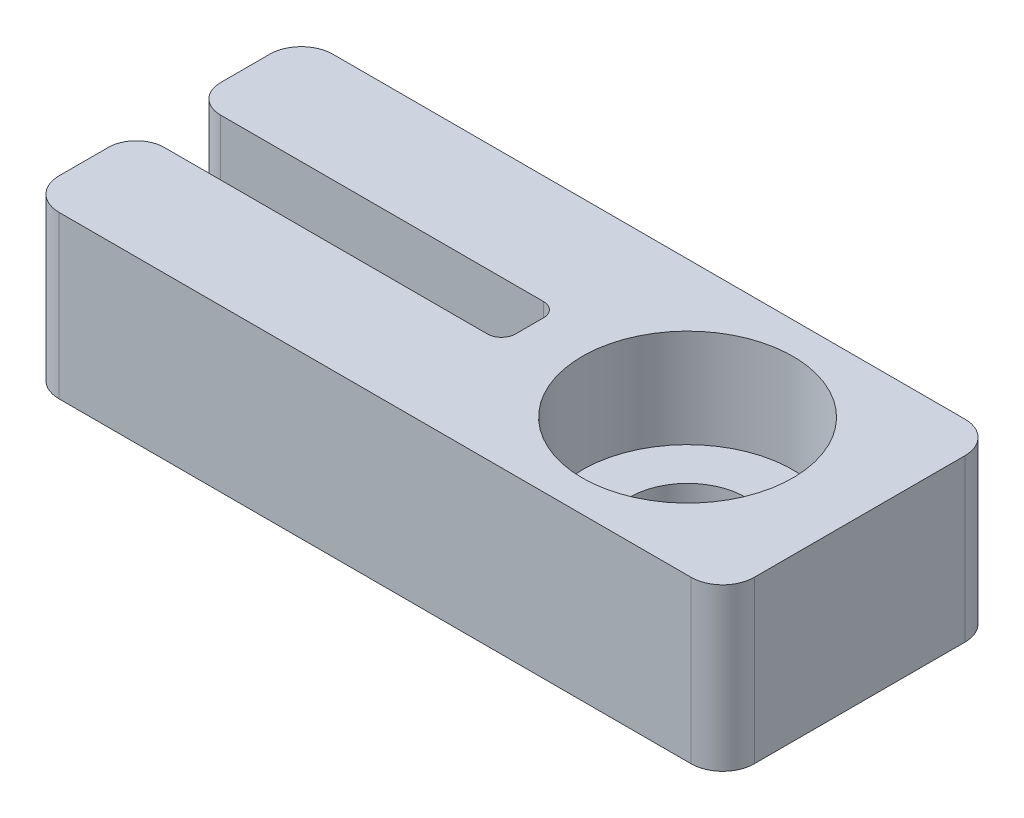
SolidWorks part; units mm, degrees
ref_plane "前视基准面" through (0, 0, 0) normal (0, 0, 1) x (1, 0, 0)
ref_plane "上视基准面" through (0, 0, 0) normal (0, 1, 0) x (1, 0, 0)
ref_plane "右视基准面" through (0, 0, 0) normal (1, 0, 0) x (0, 0, -1)
other "Configuration Table"
sketch "草图1" plane through (0, 0, 0) normal (0, 1, 0) x (1, 0, 0)
  line L0 (-9.9, -3) -> (-9.9, 3)
  line L1 (-9, -4) -> (9, -4) construction
  line L2 (-10, -3) -> (-10, 3) construction
  line L3 (-9, 4) -> (9, 4) construction
  line L4 (10, -3) -> (10, 3) construction
  line L5 (-10, -4) -> (10, 4) construction
  line L6 (-10, 4) -> (10, -4) construction
  line L7 (-9, 3.9) -> (9, 3.9)
  line L8 (9.9, -3) -> (9.9, 3)
  line L9 (-9, -3.9) -> (9, -3.9)
  arc A0 (9, 4) -> (10, 3) centre (9, 3) cw construction
  arc A1 (10, -3) -> (9, -4) centre (9, -3) cw construction
  arc A2 (-9, -4) -> (-10, -3) centre (-9, -3) cw construction
  arc A3 (-10, 3) -> (-9, 4) centre (-9, 3) cw construction
  circle A4 centre (5, 0) radius 1.65
  arc A5 (-9.9, 3) -> (-9, 3.9) centre (-9, 3) cw
  arc A6 (9, 3.9) -> (9.9, 3) centre (9, 3) cw
  arc A7 (9.9, -3) -> (9, -3.9) centre (9, -3) cw
  arc A8 (-9, -3.9) -> (-9.9, -3) centre (-9, -3) cw
  point P0 (0, 0)
  dimension "D1" = 1
  dimension "D2" = 0.1
extrude "凸台-拉伸1" add sketch "草图1" along normal blind 4.6
sketch "草图2" plane through (0, 4.6, 0) normal (0, 1, 0) x (1, 0, 0)
  line L1 (-10.1, 0.8) -> (0.1, 0.8)
  line L2 (-10.5, 0.4) -> (-10.5, -0.4)
  line L3 (-10.1, -0.8) -> (0.1, -0.8)
  line L4 (0.5, 0.4) -> (0.5, -0.4)
  line L5 (-10.5, 0.8) -> (0.5, -0.8) construction
  line L6 (-10.5, -0.8) -> (0.5, 0.8) construction
  arc A0 (0.1, -0.8) -> (0.5, -0.4) centre (0.1, -0.4) ccw
  arc A1 (0.5, 0.4) -> (0.1, 0.8) centre (0.1, 0.4) ccw
  arc A2 (-10.1, -0.8) -> (-10.5, -0.4) centre (-10.1, -0.4) cw
  arc A3 (-10.5, 0.4) -> (-10.1, 0.8) centre (-10.1, 0.4) cw
  point P0 (-5, 0)
  dimension "D3" = 0.4
  dimension "D1" = 11
  dimension "D2" = 1.6
extrude "切除-拉伸1" cut sketch "草图2" against normal up to surface (4.6 mm away) up to face at (0, 0, 0)
fillet "圆角1" radius 0.8 2 edges at (-9.9, 2.3, 0.8) (-9.9, 2.3, -0.8)
sketch "草图3" plane through (0, 4.6, 0) normal (0, 1, 0) x (1, 0, 0)
  circle A0 centre (5, 0) radius 3
extrude "切除-拉伸2" cut sketch "草图3" against normal blind 2.8
